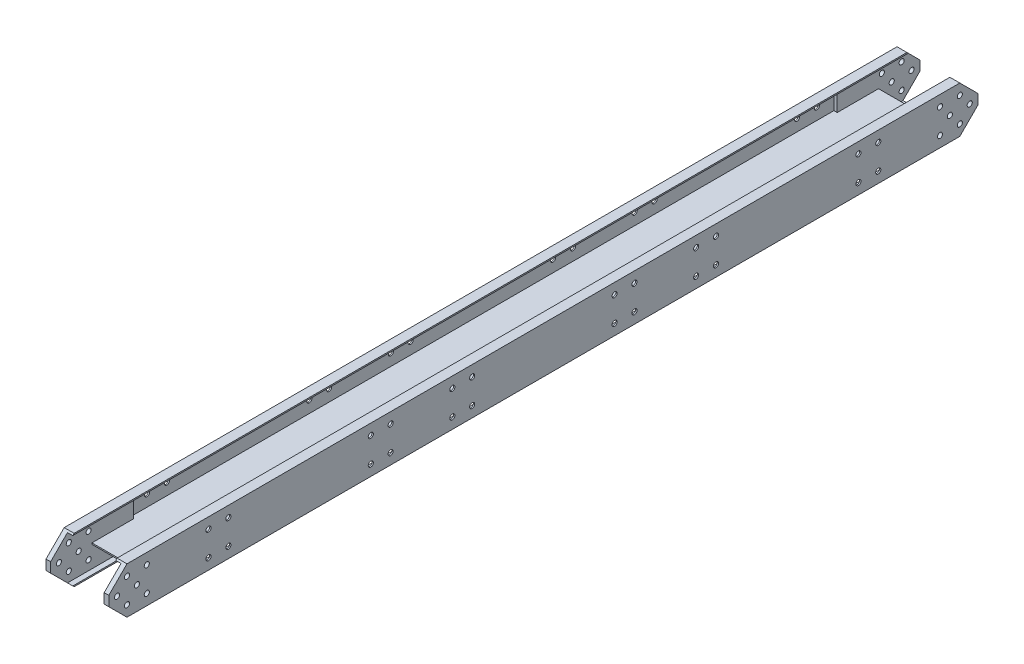
SolidWorks part; units mm, degrees
ref_plane "前视基准面" through (0, 0, 0) normal (0, 0, 1) x (1, 0, 0)
ref_plane "上视基准面" through (0, 0, 0) normal (0, 1, 0) x (1, 0, 0)
ref_plane "右视基准面" through (0, 0, 0) normal (1, 0, 0) x (0, 0, -1)
sketch "草图1" plane through (0, 0, 0) normal (0, 0, 1) x (1, 0, 0)
  line L0 (-1000, 0) -> (49000, 0) construction
  line L1 (0, -1000) -> (0, 49000) construction
  line L3 (-190, 140) -> (-130, 140)
  line L4 (-190, 140) -> (-190, -140)
  line L5 (-190, -140) -> (-130, -140)
  line L6 (-130, 140) -> (-130, -140)
  line L7 (-182, 132) -> (-130, 132)
  line L8 (-182, 132) -> (-182, -132)
  line L9 (-182, -132) -> (-130, -132)
  line L10 (-130, 132) -> (-130, -132)
  dimension "D1" = 280
  dimension "D2" = 140
  dimension "D3" = 8
  dimension "D4" = 60
  dimension "D5" = 8
  dimension "D6" = 8
  dimension "D7" = 190
extrude "拉伸1" add sketch "草图1" along normal blind 2630 contours L9 L8 L7 L6 L3 L4 L5
sketch "草图2" plane through (-182, 0, 0) normal (1, 0, 0) x (0, 0, -1)
  line L0 (-2130, 132) -> (-2130, -132)
  line L1 (-2630, 132) -> (0, 132) construction
  line L2 (-2630, 132) -> (-2630, -132) construction
  line L3 (-2630, -132) -> (0, -132) construction
  line L8 (0, -132) -> (0, 132)
  line L9 (0, 132) -> (-2630, 132)
  line L10 (-2630, 132) -> (-2630, -132)
  line L11 (-2630, -132) -> (0, -132)
  line L13 (-2130, 132) -> (-2630, 132)
  line L14 (-2630, 132) -> (-2630, -132)
  line L15 (-2630, -132) -> (-2130, -132)
  dimension "D1" = 500
  dimension "D2" = 0
extrude "拉伸2" add sketch "草图2" along normal blind 20
sketch "草图4" plane through (-182, 0, 0) normal (1, 0, 0) x (0, 0, -1)
  line L1 (-3130, 0) -> (46870, 0) construction
  line L2 (-2130, -132) -> (-2130, 132) construction
  line L3 (0, 132) -> (0, -132) construction
  line L4 (-2380, 4) -> (0, 4)
  line L6 (-2380, 4) -> (-2380, -4)
  line L7 (-2380, -4) -> (0, -4)
  line L8 (0, 4) -> (0, -4)
  line L9 (-2630, 132) -> (-2630, -132) construction
  point P5 (-2130, 0)
  dimension "D1" = 4
  dimension "D2" = 8
  dimension "D3" = 250
extrude "拉伸4" add sketch "草图4" along normal blind 182
mirror "镜向2" about plane through (0, -4, 2380) normal (1, 0, 0) of bodies 105
sketch "草图5" plane through (190, 0, 0) normal (1, 0, 0) x (0, 0, -1)
  line L0 (-3630, 0) -> (46370, 0) construction
  line L1 (-2630, 140) -> (-2630, -140) construction
  line L2 (-2520, -75) -> (-2400, -75) construction
  line L3 (-2580, 0) -> (-2460, 0) construction
  line L4 (-2520, -75) -> (-2026.5, -75) construction
  line L5 (-2026.5, 75) -> (-1044.5, 75) construction
  line L6 (-924.5, -75) -> (-431, -75) construction
  line L7 (-2520, 140) -> (-2630, 30)
  line L8 (-2630, 140) -> (0, 140) construction
  line L9 (-2520, -140) -> (-2630, -30)
  circle A0 centre (-2520, 75) radius 15.5
  circle A1 centre (-2580, 0) radius 15.5
  circle A2 centre (-2520, -75) radius 15.5
  circle A3 centre (-2400, -75) radius 15.5
  circle A4 centre (-2400, 75) radius 15.5
  circle A5 centre (-2460, 0) radius 15.5
  circle A6 centre (-2026.5, -75) radius 15.5
  circle A7 centre (-2026.5, 75) radius 15.5
  circle A8 centre (-1906.5, 75) radius 15.5
  circle A9 centre (-1906.5, -75) radius 15.5
  circle A10 centre (-1044.5, 75) radius 15.5
  circle A11 centre (-924.5, 75) radius 15.5
  circle A12 centre (-924.5, -75) radius 15.5
  circle A13 centre (-1044.5, -75) radius 15.5
  circle A14 centre (-431, -75) radius 15.5
  circle A15 centre (-551, -75) radius 15.5
  circle A16 centre (-551, 75) radius 15.5
  circle A17 centre (-431, 75) radius 15.5
  point P7 (-2630, 0)
  line M2 (0, 140) -> (-2630, 140)
  line M3 (-2630, 140) -> (-2630, -140)
  line M4 (-2630, -140) -> (0, -140)
  dimension "D1" = 31
  dimension "D3" = 31
  dimension "D2" = 75
  dimension "D4" = 50
  dimension "D5" = 60
  dimension "D6" = 120
  dimension "D7" = 120
  dimension "D8" = 493.5
  dimension "D9" = 982
  dimension "D10" = 493.5
  dimension "D11" = 110
  dimension "D12" = 110
extrude "拉伸6" cut sketch "草图5" against normal through all contours L7 M2 M3 | L9 M4 M3 | A1 | A0 | A4 | A3 | A6 | A7 | A8 | A9 | A2 | A5 | A10 | A11 | A13 | A12 | A16 | A17 | A15 | A14
mirror "镜向3" about plane through (0, 0, 0) normal (0, 0, 1) of bodies 107
